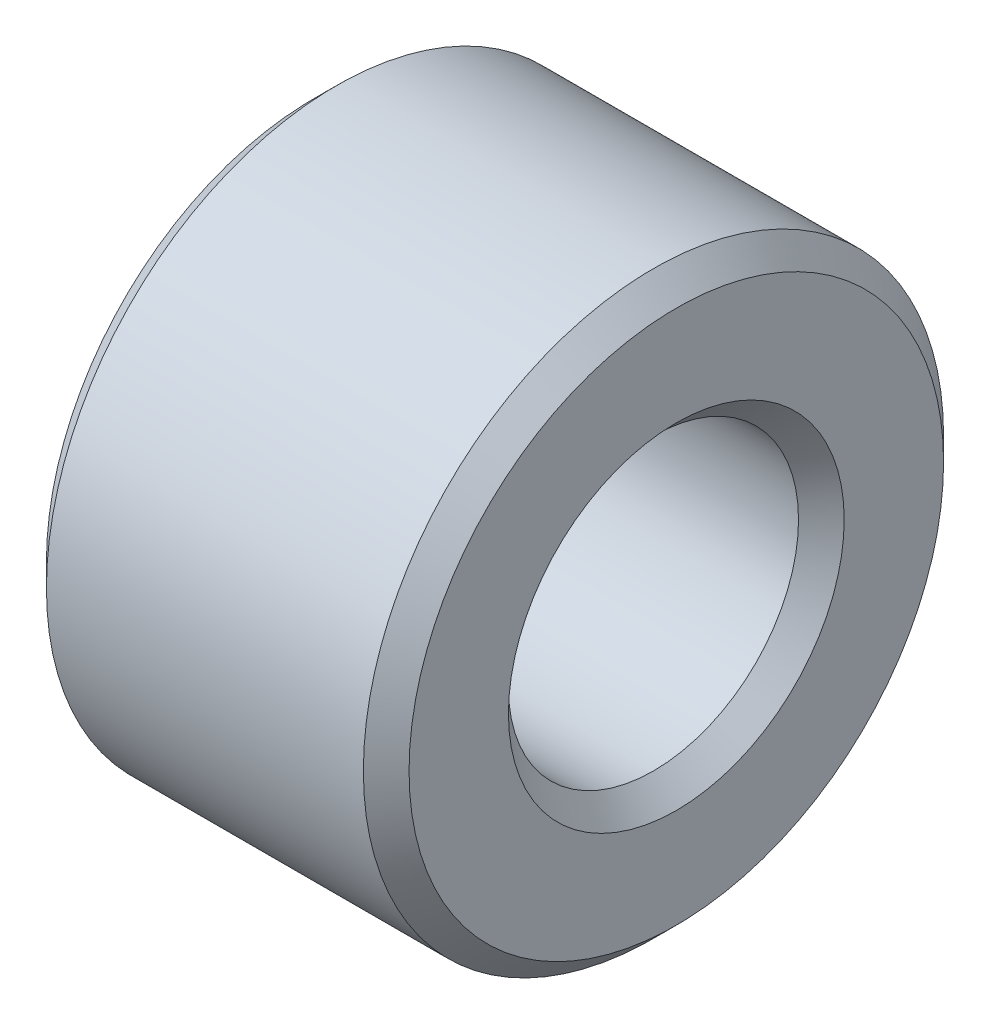
SolidWorks part; units mm, degrees
ref_plane "Front Plane" through (0, 0, 0) normal (0, 0, 1) x (1, 0, 0)
ref_plane "Top Plane" through (0, 0, 0) normal (0, 1, 0) x (1, 0, 0)
ref_plane "Right Plane" through (0, 0, 0) normal (1, 0, 0) x (0, 0, -1)
sketch "Sketch1" plane through (0, 0, 0) normal (1, 0, 0) x (0, 0, -1)
  circle A0 centre (0, 0) radius 25.4
  circle A1 centre (0, 0) radius 12.7
  dimension "D1" = 25.4
  dimension "D2" = 50.8
extrude "Boss-Extrude1" add sketch "Sketch1" along normal blind 31.75
chamfer "Chamfer1" distance 2 angle 45 4 edges at (0, 0, -25.4) (31.75, 0, -25.4) (0, 0, -12.7) (31.75, 0, -12.7)
